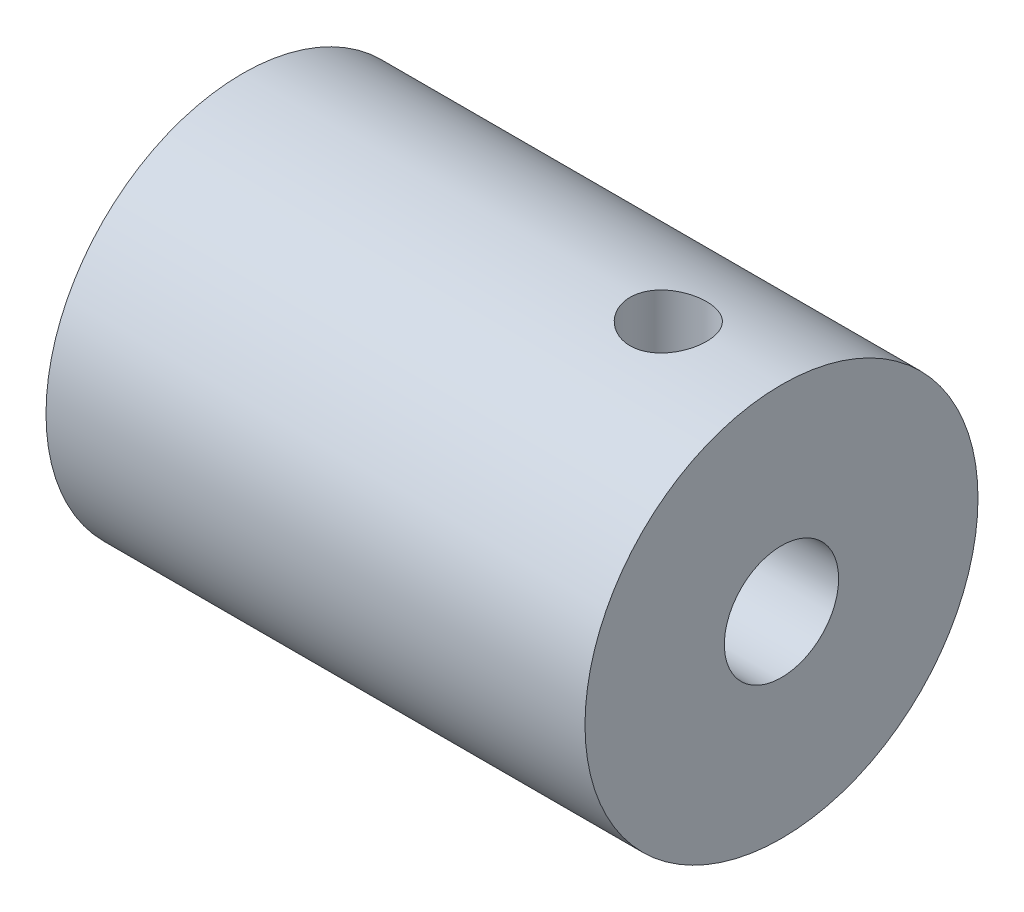
SolidWorks part; units mm, degrees
material "Plain Carbon Steel"
ref_plane "Front Plane" through (0, 0, 0) normal (0, 0, 1) x (1, 0, 0)
ref_plane "Top Plane" through (0, 0, 0) normal (0, 1, 0) x (1, 0, 0)
ref_plane "Right Plane" through (0, 0, 0) normal (1, 0, 0) x (0, 0, -1)
sketch "Sketch1" plane through (0, 0, 0) normal (1, 0, 0) x (0, 0, -1)
  circle A0 centre (0, 0) radius 6.9453
  dimension "D1" = 13.8906
extrude "Boss-Extrude1" add sketch "Sketch1" along normal blind 19.05
hole_wizard "#21 (0.159) Diameter Hole1" positions "Sketch4" profile "Sketch3" hole size "#21" standard "ANSI Inch"
sketch "Sketch4" plane through (19.05, 0, 0) normal (1, 0, 0) x (0, 0, -1)
  point P0 (0, 0)
sketch "Sketch3" plane through (19.05, 0, 0) normal (0, 1, 0) x (0, 0, -1)
  line L0 (0, 0) -> (0, 8.2133)
  line L1 (0, 8.2133) -> (2.0193, 7)
  line L2 (2.0193, 7) -> (2.0193, 0)
  line L5 (2.0193, 0) -> (0, 0)
  line L10 (0, 8.2133) -> (-2.0193, 7) construction
  line L11 (0, -6.35) -> (0, 107.95) construction
  dimension "Hole Dia." = 4.0386
  dimension "Hole Depth" = 7
  dimension "Drill Angle" = 118
hole_wizard "#6-32 Tapped Hole1" positions "Sketch6" profile "Sketch5" tap size "#6-32" standard "ANSI Inch"
sketch "Sketch6" plane through (0, 0, 0) normal (0, 1, 0) x (1, 0, 0)
  line L0 (19.05, -6.9453) -> (19.05, 6.9453) construction
  point P0 (15.05, 0)
  dimension "D1" = 4
sketch "Sketch5" plane through (15.05, 0, 0) normal (1, 0, 0) x (0, 0, -1)
  line L0 (0, 0) -> (0, 6.9453)
  line L1 (0, 6.9453) -> (1.3525, 6.9453)
  line L2 (1.3525, 6.9453) -> (1.3525, 0)
  line L5 (1.3525, 0) -> (0, 0)
  line L11 (0, -6.35) -> (0, 107.95) construction
  dimension "Thru Tap Drill Dia." = 2.7051
  dimension "Thru Tap Drill Depth" = 6.9453
cosmetic thread "Hole Thread1" parameters "D2"=3.5052
